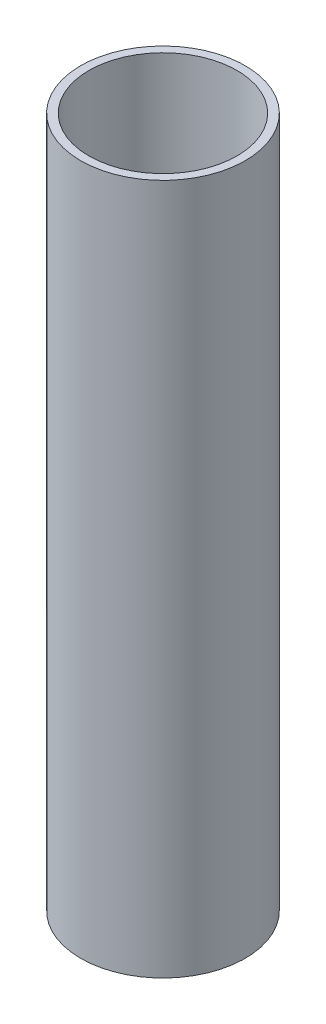
SolidWorks part; units mm, degrees
ref_plane "Front Plane" through (0, 0, 0) normal (0, 0, 1) x (1, 0, 0)
ref_plane "Top Plane" through (0, 0, 0) normal (0, 1, 0) x (1, 0, 0)
ref_plane "Right Plane" through (0, 0, 0) normal (1, 0, 0) x (0, 0, -1)
sketch "Sketch2" plane through (0, 0, 0) normal (0, 1, 0) x (1, 0, 0)
  circle A0 centre (0, 0) radius 12.7
  dimension "D1" = 25.4
extrude "Boss-Extrude1" add sketch "Sketch2" against normal blind 106.6
sketch "Sketch3" plane through (0, 0, 0) normal (0, 1, 0) x (1, 0, 0)
  circle A0 centre (0, 0) radius 11.43
  dimension "D1" = 22.86
extrude "Cut-Extrude1" cut sketch "Sketch3" against normal blind 101.6
